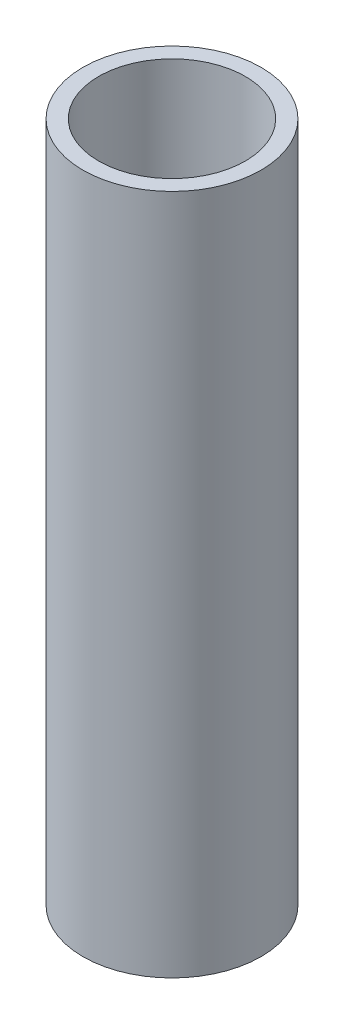
SolidWorks part; units mm, degrees
ref_plane "Front Plane" through (0, 0, 0) normal (0, 0, 1) x (1, 0, 0)
ref_plane "Top Plane" through (0, 0, 0) normal (0, 1, 0) x (1, 0, 0)
ref_plane "Right Plane" through (0, 0, 0) normal (1, 0, 0) x (0, 0, -1)
sketch "Sketch1" plane through (0, 0, 0) normal (0, 1, 0) x (1, 0, 0)
  circle A0 centre (0, 0) radius 14
  circle A1 centre (0, 0) radius 17
  dimension "D1" = 28
  dimension "D2" = 34
extrude "Boss-Extrude1" add sketch "Sketch1" along normal blind 130
